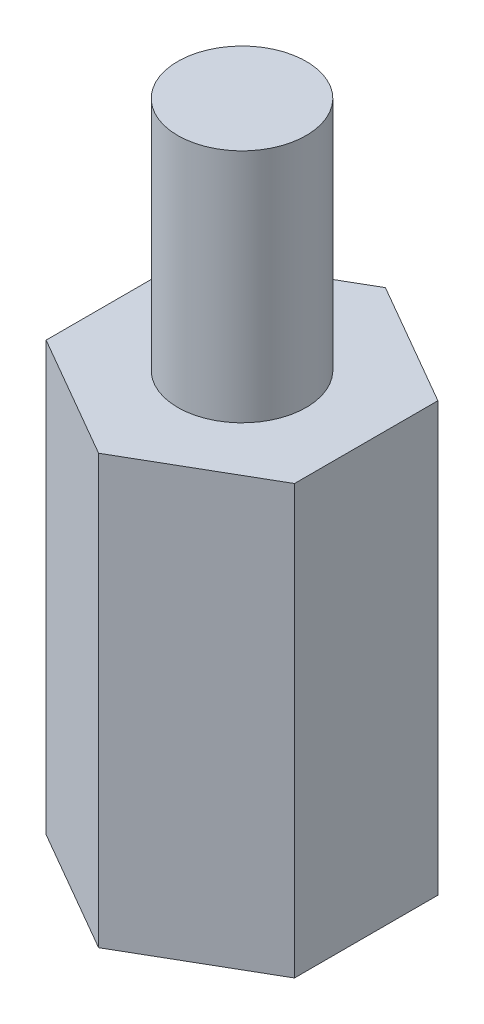
SolidWorks part; units mm, degrees
ref_plane "Front Plane" through (0, 0, 0) normal (0, 0, 1) x (1, 0, 0)
ref_plane "Top Plane" through (0, 0, 0) normal (0, 1, 0) x (1, 0, 0)
ref_plane "Right Plane" through (0, 0, 0) normal (1, 0, 0) x (0, 0, -1)
sketch "Sketch1" plane through (0, 0, 0) normal (0, 1, 0) x (1, 0, 0)
  line L1 (0, -3.3486) -> (2.9, -1.6743)
  line L2 (2.9, -1.6743) -> (2.9, 1.6743)
  line L3 (2.9, 1.6743) -> (0, 3.3486)
  line L4 (0, 3.3486) -> (-2.9, 1.6743)
  line L5 (-2.9, 1.6743) -> (-2.9, -1.6743)
  line L6 (-2.9, -1.6743) -> (0, -3.3486)
  circle A0 centre (0, 0) radius 2.9 construction
  circle A1 centre (0, 0) radius 1.5
  dimension "D2" = 3
  dimension "D1" = 5.8
extrude "Boss-Extrude1" add sketch "Sketch1" along normal mid plane 10
sketch "Sketch2" plane through (0, 5, 0) normal (0, 1, 0) x (1, 0, 0)
  circle A0 centre (0, 0) radius 1.5 construction
  circle A1 centre (0, 0) radius 1.5
extrude "Boss-Extrude2" add sketch "Sketch2" along normal blind 5.5 separate body
